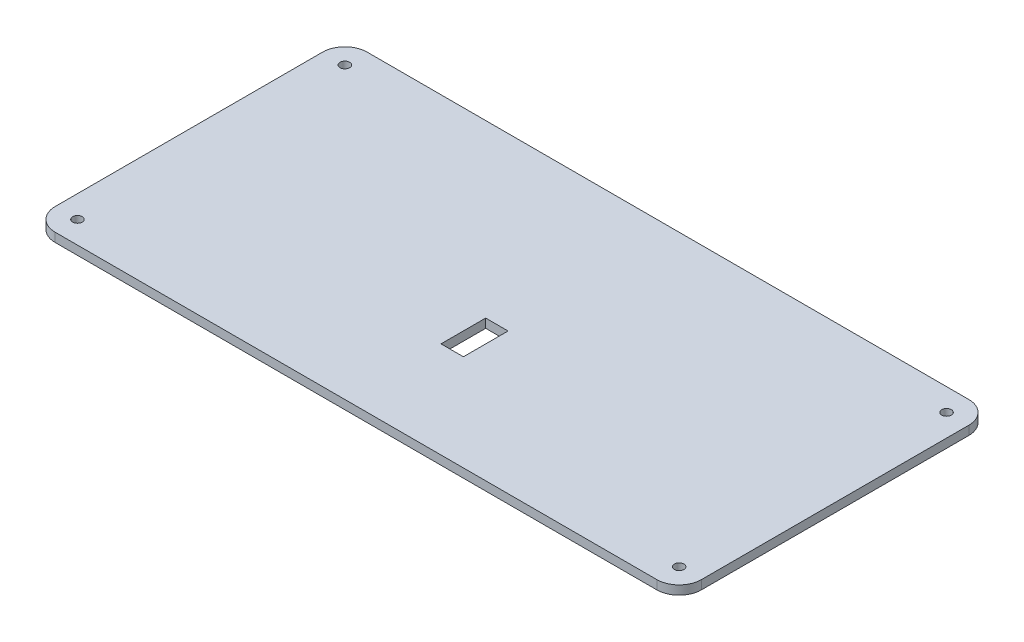
SolidWorks part; units mm, degrees
ref_plane "Front Plane" through (0, 0, 0) normal (0, 0, 1) x (1, 0, 0)
ref_plane "Top Plane" through (0, 0, 0) normal (0, 1, 0) x (1, 0, 0)
ref_plane "Right Plane" through (0, 0, 0) normal (1, 0, 0) x (0, 0, -1)
sketch "Sketch1" plane through (0, 0, 0) normal (0, 1, 0) x (1, 0, 0)
  line L0 (0, 0) -> (145, 0) construction
  line L1 (145, 0) -> (145, -60)
  line L2 (135, -70) -> (0, -70)
  line L3 (0, -70) -> (0, 0)
  line L4 (0, 0) -> (145, 0)
  arc A0 (135, -70) -> (145, -60) centre (135, -60) ccw
  circle A1 centre (135, -60) radius 2.15
  point P7 (145, -70)
  dimension "D4" = 10
  dimension "D5" = 4.3
  dimension "D1" = 145
  dimension "D2" = 70
  dimension "D3" = 145
extrude "Boss-Extrude1" add sketch "Sketch1" along normal blind 4 contours L2 A0 L1 L4 L3 A1
mirror "Mirror1" about plane through (0, 0, 0) normal (1, 0, 0) of "Boss-Extrude1"
mirror "Mirror2" about plane through (0, 0, 0) normal (0, 0, 1) of "Mirror1", "Boss-Extrude1"
sketch "Sketch2" plane through (0, 4, 0) normal (0, 1, 0) x (1, 0, 0)
  line L0 (-4.55, -26.3091) -> (4.45, -26.3091) construction
  line L1 (4.45, -26.3091) -> (4.5, -7.2591) construction
  line L2 (4.5, -7.2591) -> (-4.5, -7.2591) construction
  line L3 (4.5, -14.3091) -> (4.5, -7.2591) construction
  line L4 (4.5, -7.2591) -> (-4.5, -7.2591) construction
  line L5 (-4.5, -7.2591) -> (-4.55, -26.3091) construction
  line L6 (-4.55, -26.3091) -> (-5.05, -26.3091) construction
  line L7 (-5.05, -26.3091) -> (-5.05, -26.8091) construction
  line L8 (4.5, -7.2591) -> (4.5, -6.7591) construction
  line L9 (4.5, -6.7591) -> (5, -6.7591) construction
  line L11 (-5.05, -26.8091) -> (5, -26.8091)
  line L12 (-5.05, -26.8091) -> (-5.05, -6.7591)
  line L13 (-5.05, -6.7591) -> (5, -6.7591)
  line L14 (5, -26.8091) -> (5, -6.7591)
  dimension "D1" = 0.5
  dimension "D2" = 0.5
  dimension "D3" = 0.5
  dimension "D4" = 0.5
extrude "Cut-Extrude5" cut sketch "Sketch2" against normal through all
